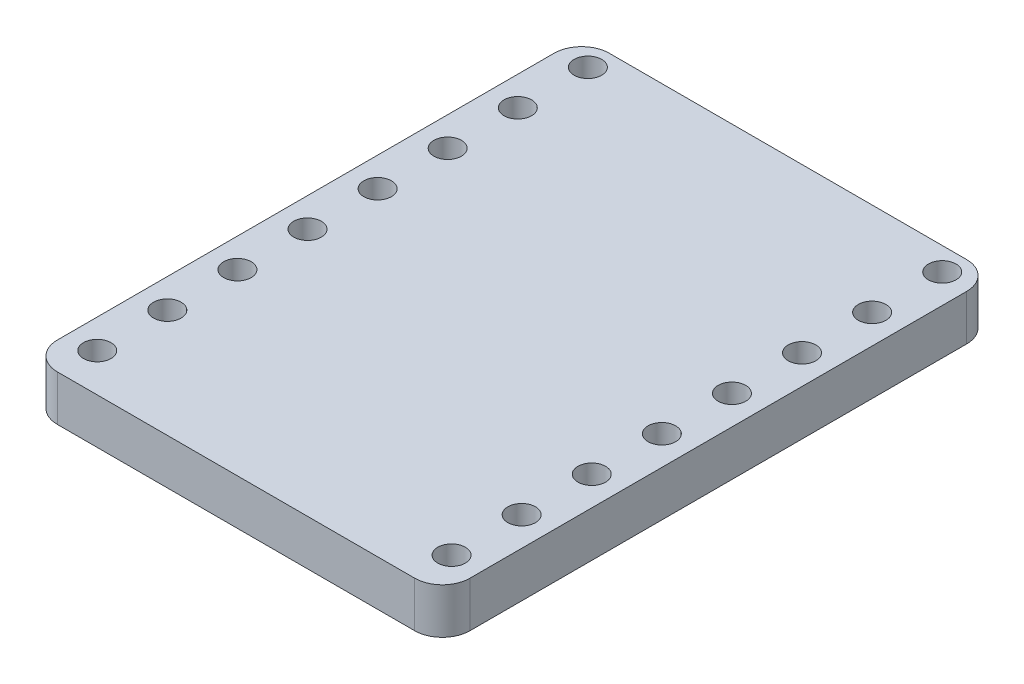
SolidWorks part; units mm, degrees
ref_plane "Front Plane" through (0, 0, 0) normal (0, 0, 1) x (1, 0, 0)
ref_plane "Top Plane" through (0, 0, 0) normal (0, 1, 0) x (1, 0, 0)
ref_plane "Right Plane" through (0, 0, 0) normal (1, 0, 0) x (0, 0, -1)
sketch "Sketch1" plane through (0, 0, 0) normal (0, 1, 0) x (1, 0, 0)
  line L0 (-8.96, 0) -> (8.96, 0) construction
  line L1 (0, 11.43) -> (0, -11.43) construction
  line L3 (-8.96, 11.43) -> (8.96, 11.43)
  line L4 (-8.96, 11.43) -> (-8.96, -11.43)
  line L5 (-8.96, -11.43) -> (8.96, -11.43)
  line L6 (8.96, 11.43) -> (8.96, -11.43)
  line L7 (-8.96, 11.43) -> (8.96, -11.43) construction
  line L8 (-8.96, -11.43) -> (8.96, 11.43) construction
  point P0 (0, 0)
  point P4 (0, 0)
  point P8 (0, 0)
  dimension "D2" = 17.92
  dimension "D1" = 22.86
extrude "Boss-Extrude1" add sketch "Sketch1" along normal mid plane 1.65
sketch "Sketch3" plane through (0, 0, 0) normal (0, 1, 0) x (1, 0, 0)
  line L0 (-8.96, 11.43) -> (-8.96, -11.43) construction
  line L1 (-8.96, -11.43) -> (8.96, -11.43) construction
  circle A0 centre (-6.42, -8.89) radius 0.5
  dimension "D1" = 1
  dimension "D2" = 2.54
  dimension "D3" = 2.54
extrude "Cut-Extrude1" cut sketch "Sketch3" against normal through all both and the other way through all
pattern_linear "LPattern1" count 8 spacing 2.54 along (0, 0, -1) count 2 spacing 12.84 along (1, 0, 0) of "Cut-Extrude1"
sketch "Sketch4" plane through (0, 0.825, 0) normal (0, 1, 0) x (1, 0, 0)
  line L0 (-9.475, 11.72) -> (9.475, 11.72)
  line L1 (-7.475, 9.72) -> (7.475, 9.72)
  line L2 (-7.475, 9.72) -> (-7.475, -10.28)
  line L3 (-7.475, -10.28) -> (7.475, -10.28)
  line L4 (7.475, 9.72) -> (7.475, -10.28)
  line L5 (9.475, 11.72) -> (9.475, -12.28)
  line L6 (-9.475, -12.28) -> (9.475, -12.28)
  line L7 (-9.475, 11.72) -> (-9.475, -12.28)
  point P6 (0, -10.28)
  dimension "D1" = 20
  dimension "D2" = 14.95
  dimension "D3" = 9.72
  dimension "D4" = 2
extrude "Cut-Extrude2" cut sketch "Sketch4" against normal through all
fillet "Fillet1" radius 1 4 edges at (7.475, 0, 10.28) (7.475, 0, -9.72) (-7.475, 0, -9.72) (-7.475, 0, 10.28)
equation "\"D1@Sketch1\"=2.54*9"
equation "\"D2@Sketch1\"=12.84mm+2*2.54"
